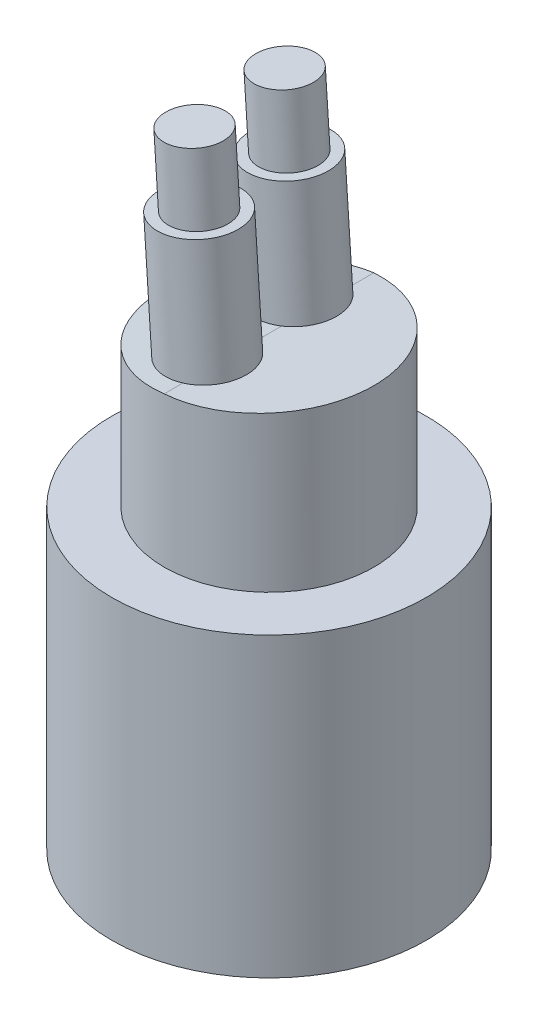
SolidWorks part; units mm, degrees
ref_plane "Alzado" through (0, 0, 0) normal (0, 0, 1) x (1, 0, 0)
ref_plane "Planta" through (0, 0, 0) normal (0, 1, 0) x (1, 0, 0)
ref_plane "Vista lateral" through (0, 0, 0) normal (1, 0, 0) x (0, 0, -1)
sketch "Croquis1" plane through (0, 0, 0) normal (0, 1, 0) x (1, 0, 0)
  circle A0 centre (0, 0) radius 9
  dimension "D1" = 18
extrude "Saliente-Extruir1" add sketch "Croquis1" along normal blind 17
sketch "Croquis2" plane through (0, 17, 0) normal (0, 1, 0) x (1, 0, 0)
  circle A0 centre (0, 0) radius 6
  dimension "D1" = 12
extrude "Saliente-Extruir2" add sketch "Croquis2" along normal blind 9
sketch "Croquis3" plane through (0, 0, 0) normal (0, 0, 1) x (1, 0, 0)
  line L0 (0, 0) -> (0, 17) construction
  line L1 (9, 17) -> (-9, 17) construction
  line L4 (-6, 26) -> (-6, 17) construction
  line L5 (-6, 24.801) -> (0, 25.6)
  line L6 (0, 25.6) -> (6, 26)
  line L7 (6, 26) -> (-6, 26)
  line L8 (-6, 26) -> (-6, 24.801)
  dimension "D1" = 8.6
extrude "Cortar-Extruir1" cut sketch "Croquis3" against normal mid plane 19
sketch "Croquis4" plane through (-1.6991, 25.4867, 0) normal (-0.0665, 0.9978, 0) x (0.9978, 0.0665, 0)
  line L0 (1.7029, 6) -> (1.7029, -6) construction
  circle A0 centre (0.6297, 2.6941) radius 2.25
  circle A1 centre (0.97, -2.8059) radius 2.25
  point P6 (1.7029, 0)
  dimension "D3" = 4.5
  dimension "D4" = 4.5
  dimension "D1" = 2.9
  dimension "D2" = 2.9
  dimension "D5" = 5.5
extrude "Saliente-Extruir3" add sketch "Croquis4" along normal blind 7
sketch "Croquis5" plane through (-2.1647, 32.4712, 0) normal (-0.0665, 0.9978, 0) x (0.9978, 0.0665, 0)
  circle A0 centre (0.6297, 2.6941) radius 1.65
  circle A1 centre (0.97, -2.8059) radius 1.65
  dimension "D1" = 3.3
extrude "Saliente-Extruir4" add sketch "Croquis5" along normal blind 4
sketch "Croquis6" plane through (0, 0, 0) normal (0, -1, 0) x (1, 0, 0)
  circle A0 centre (0, 0) radius 2.05
  dimension "D1" = 4.1
extrude "Cortar-Extruir2" cut sketch "Croquis6" against normal blind 5
